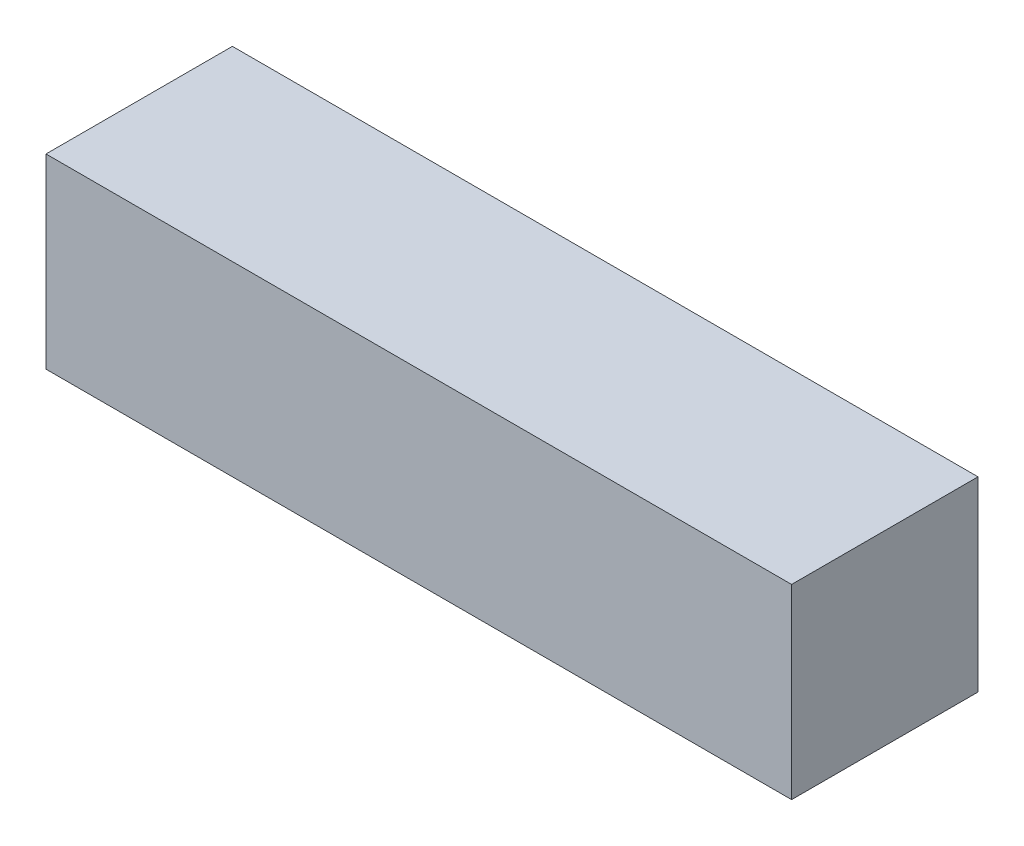
SolidWorks part; units mm, degrees
ref_plane "Front Plane" through (0, 0, 0) normal (0, 0, 1) x (1, 0, 0)
ref_plane "Top Plane" through (0, 0, 0) normal (0, 1, 0) x (1, 0, 0)
ref_plane "Right Plane" through (0, 0, 0) normal (1, 0, 0) x (0, 0, -1)
sketch "Sketch2" plane through (0, 0, 0) normal (0, 1, 0) x (1, 0, 0)
  line L1 (-10, 2.5) -> (10, 2.5)
  line L2 (-10, 2.5) -> (-10, -2.5)
  line L3 (-10, -2.5) -> (10, -2.5)
  line L4 (10, 2.5) -> (10, -2.5)
  line L5 (-10, 2.5) -> (10, -2.5) construction
  line L6 (-10, -2.5) -> (10, 2.5) construction
  point P0 (0, 0)
  dimension "D1" = 20
  dimension "D2" = 5
extrude "Boss-Extrude1" add sketch "Sketch2" along normal blind 5
